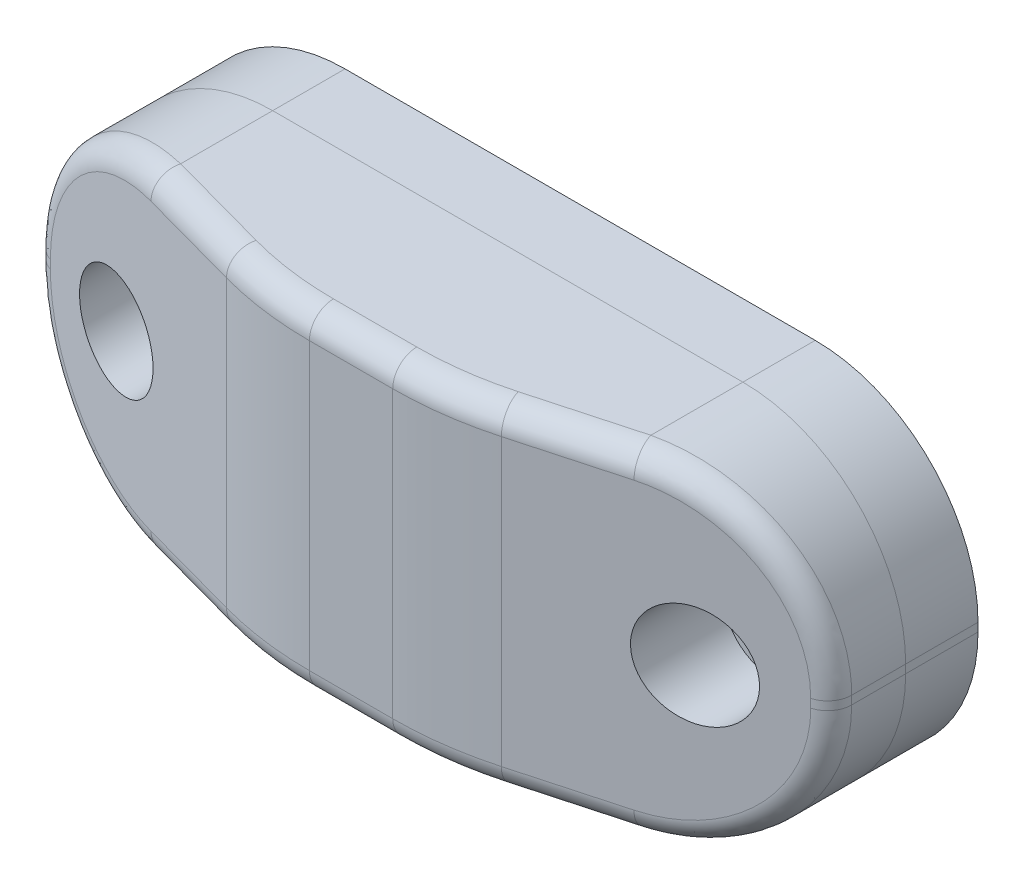
SolidWorks part; units mm, degrees
material "Custom Plastic"
ref_plane "X-Y Datum" through (0, 0, 0) normal (0, 0, 1) x (1, 0, 0)
ref_plane "X-Z Datum" through (0, 0, 0) normal (0, 1, 0) x (1, 0, 0)
ref_plane "Y-Z Datum" through (0, 0, 0) normal (1, 0, 0) x (0, 0, -1)
sketch "Sketch1" plane through (0, 0, 0) normal (0, 0, 1) x (1, 0, 0)
  line L0 (-24, 0) -> (24, 0) construction
  line L1 (-19.5, 13.85) -> (19.5, 13.85)
  line L2 (-33, 0.35) -> (-33, -0.35)
  line L3 (-19.5, -13.85) -> (19.5, -13.85)
  line L4 (33, 0.35) -> (33, -0.35)
  line L5 (-33, 13.85) -> (33, -13.85) construction
  line L6 (-33, -13.85) -> (33, 13.85) construction
  circle A0 centre (-24, 0) radius 2.3
  circle A1 centre (24, 0) radius 2.3
  arc A2 (19.5, 13.85) -> (33, 0.35) centre (19.5, 0.35) cw
  arc A3 (19.5, -13.85) -> (33, -0.35) centre (19.5, -0.35) ccw
  arc A4 (-19.5, 13.85) -> (-33, 0.35) centre (-19.5, 0.35) ccw
  arc A5 (-33, -0.35) -> (-19.5, -13.85) centre (-19.5, -0.35) ccw
  point P0 (0, 0)
  point P9 (0, 0)
  dimension "D4" = 4.6
  dimension "D5" = 13.5
  dimension "D1" = 27.7
  dimension "D2" = 66
  dimension "D3" = 48
extrude "Boss-Extrude1" add sketch "Sketch1" along normal blind 19
sketch "Sketch2" plane through (0, -13.85, 0) normal (0, -1, 0) x (1, 0, 0)
  line L0 (19.5, 0) -> (33, 0) construction
  line L1 (33, 0) -> (33, 19) construction
  line L2 (33, 19) -> (19.5, 19) construction
  line L3 (-19.5, 0) -> (19.5, 0) construction
  line L4 (19.5, 19) -> (-19.5, 19) construction
  line L5 (-33, 0) -> (-19.5, 0) construction
  line L6 (-19.5, 19) -> (-33, 19) construction
  line L7 (-33, 19) -> (-33, 0) construction
  line L8 (19.5, 0) -> (33, 0)
  line L9 (33, 0) -> (33, 19)
  line L10 (33, 19) -> (19.5, 19)
  line L11 (-19.5, 0) -> (19.5, 0)
  line L12 (19.5, 19) -> (-19.5, 19)
  line L13 (-33, 0) -> (-19.5, 0)
  line L14 (-19.5, 19) -> (-33, 19)
  line L15 (-33, 19) -> (-33, 0)
  line L16 (-33, 12) -> (-7.5, 19)
  line L17 (-7.5, 19) -> (7.5, 19)
  line L18 (0, -10.45) -> (0, 10.45) construction
  line L19 (33, 12) -> (7.5, 19)
  point P10 (-2.7538, 19)
  point P13 (0, 19)
  line M11 (19.5, 0) -> (19.5, 19)
  line M12 (19.5, 19) -> (-19.5, 19)
  line M13 (-19.5, 19) -> (-19.5, 0)
  dimension "D1" = 12
  dimension "D2" = 15
extrude "Cut-Extrude1" cut sketch "Sketch2" against normal through all contours L16 L12 M13 | L15 L16 L14 M13 | L19 M11 M12 | L19 L9 L10 M11
fillet "Fillet1" radius 30 2 edges at (7.5, 0, 19) (-7.5, 0, 19)
fillet "Fillet2" radius 2 16 edges at (-29.0459, -9.8959, 13.0854) (-33, 0, 12) (-29.0459, 9.8959, 13.0854) (-15.4493, 13.85, 16.8178) (-7.4638, 13.85, 18.7312) (0, 13.85, 19) (7.4638, 13.85, 18.7312) (15.4493, 13.85, 16.8178) (29.0459, 9.8959, 13.0854) (33, 0, 12) (29.0459, -9.8959, 13.0854) (15.4493, -13.85, 16.8178) (7.4638, -13.85, 18.7312) (0, -13.85, 19) (-7.4638, -13.85, 18.7312) (-15.4493, -13.85, 16.8178)
sketch "Sketch3" plane through (0, 0, 19) normal (0, 0, 1) x (1, 0, 0)
  circle A0 centre (-24, 0) radius 4.2
  circle A1 centre (24, 0) radius 4.2
  dimension "D1" = 8.4
extrude "Cut-Extrude2" cut sketch "Sketch3" against normal offset from surface (11 mm away) 8 up to face at (-21.7, 0, 0)
sketch "Sketch4" plane through (0, 0, 0) normal (0, 0, -1) x (-1, 0, 0)
  line L1 (-4.5, 6.5) -> (4.5, 6.5)
  line L2 (-4.5, 6.5) -> (-4.5, -6.5)
  line L3 (-4.5, -6.5) -> (4.5, -6.5)
  line L4 (4.5, 6.5) -> (4.5, -6.5)
  line L5 (-4.5, 6.5) -> (4.5, -6.5) construction
  line L6 (-4.5, -6.5) -> (4.5, 6.5) construction
  point P0 (0, 0)
  dimension "D1" = 9
  dimension "D2" = 13
extrude "Boss-Extrude2" add sketch "Sketch4" along normal blind 1
ref_plane "Plane1" through (0, 0, 6) normal (0, 0, -1) x (-1, 0, 0)
split line "Split Line1"
